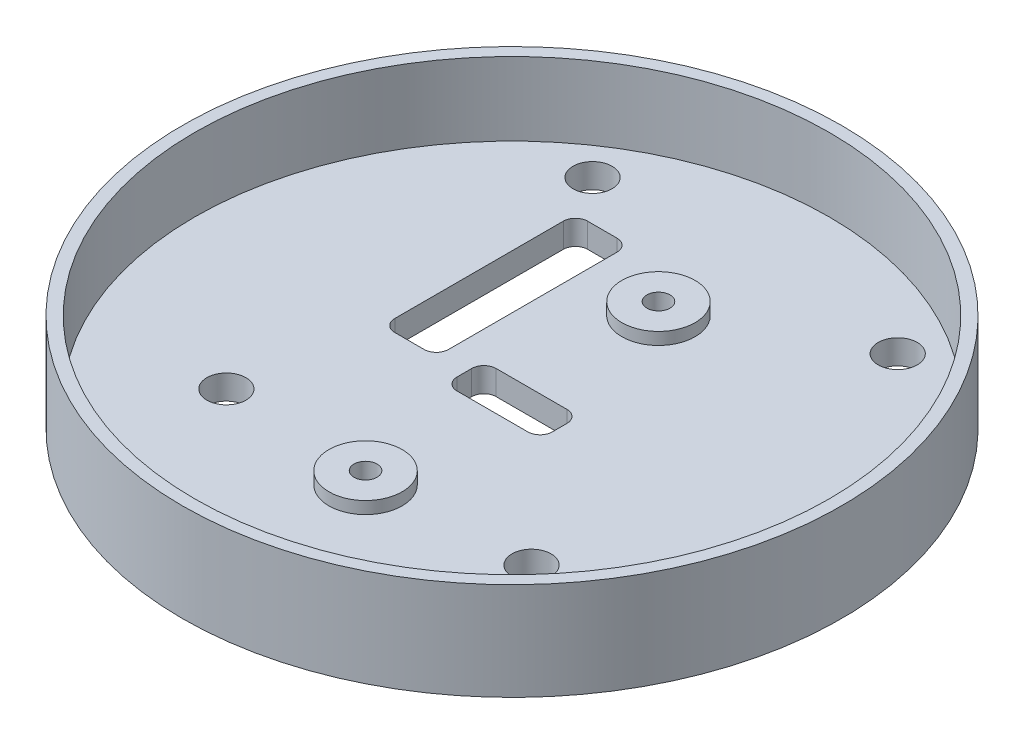
SolidWorks part; units mm, degrees
ref_plane "Front Plane" through (0, 0, 0) normal (0, 0, 1) x (1, 0, 0)
ref_plane "Top Plane" through (0, 0, 0) normal (0, 1, 0) x (1, 0, 0)
ref_plane "Right Plane" through (0, 0, 0) normal (1, 0, 0) x (0, 0, -1)
sketch "Sketch1" plane through (0, 0, 0) normal (0, 1, 0) x (1, 0, 0)
  circle A0 centre (0, 0) radius 34.29
  dimension "D1" = 68.58
extrude "Boss-Extrude1" add sketch "Sketch1" along normal blind 10.16
sketch "Sketch2" plane through (0, 10.16, 0) normal (0, 1, 0) x (1, 0, 0)
  circle A0 centre (0, 0) radius 33.02
  circle A1 centre (0, 0) radius 34.29 construction
  dimension "D1" = 66.04
extrude "Cut-Extrude1" cut sketch "Sketch2" against normal blind 7.62
sketch "Sketch3" plane through (0, 2.54, 0) normal (0, 1, 0) x (1, 0, 0)
  line L0 (0, -15.24) -> (0, 15.24) construction
  line L2 (0, -5.588) -> (0, 5.588) construction
  circle A0 centre (0, -15.24) radius 3.81
  circle A1 centre (0, 15.24) radius 3.81
  dimension "D2" = 7.62
  dimension "D3" = 7.62
  dimension "D1" = 30.48
extrude "Boss-Extrude2" add sketch "Sketch3" along normal blind 1.27
sketch "Sketch4" plane through (0, 3.81, 0) normal (0, 1, 0) x (1, 0, 0)
  line L0 (0, 33.02) -> (0, -33.02) construction
  circle A0 centre (0, -15.24) radius 1.27
  circle A1 centre (0, 15.24) radius 1.27
  circle A2 centre (0, -15.24) radius 3.81 construction
  circle A3 centre (0, 0) radius 33.02 construction
  circle A4 centre (0, 15.24) radius 3.81 construction
  circle A5 centre (0, 0) radius 33.02 construction
  point P7 (0, -15.24)
  point P10 (0, 15.24)
  dimension "D1" = 2.54
  dimension "D2" = 2.54
sketch "Sketch8" plane through (0, 2.54, 0) normal (0, 1, 0) x (1, 0, 0)
  line L0 (0, 33.02) -> (0, -33.02) construction
  line L2 (3.683, 2.032) -> (-3.683, 2.032)
  line L3 (4.953, 0.762) -> (4.953, -0.762)
  line L4 (3.683, -2.032) -> (-3.683, -2.032)
  line L5 (-4.953, 0.762) -> (-4.953, -0.762)
  line L6 (4.953, 2.032) -> (-4.953, -2.032) construction
  line L7 (4.953, -2.032) -> (-4.953, 2.032) construction
  arc A0 (-3.683, -2.032) -> (-4.953, -0.762) centre (-3.683, -0.762) cw
  arc A1 (-3.683, 2.032) -> (-4.953, 0.762) centre (-3.683, 0.762) ccw
  arc A2 (4.953, -0.762) -> (3.683, -2.032) centre (3.683, -0.762) cw
  arc A3 (3.683, 2.032) -> (4.953, 0.762) centre (3.683, 0.762) cw
  circle A4 centre (0, 0) radius 33.02 construction
  point P2 (0, 0)
  point P4 (0, 0)
  point P22 (0, 0)
  point P23 (8.7629, 0.8368)
  dimension "D3" = 1.27
  dimension "D1" = 9.906
  dimension "D2" = 4.064
extrude "Cut-Extrude3" cut sketch "Sketch8" against normal up to next
sketch "Sketch9" plane through (0, 2.54, 0) normal (0, 1, 0) x (1, 0, 0)
  line L1 (-12.192, 0) -> (-9.144, 0)
  line L2 (-13.462, 1.27) -> (-13.462, 18.796)
  line L3 (-12.192, 20.066) -> (-9.144, 20.066)
  line L4 (-7.874, 1.27) -> (-7.874, 18.796)
  line L5 (-13.462, 0) -> (-7.874, 20.066) construction
  line L6 (-13.462, 20.066) -> (-7.874, 0) construction
  line L9 (4.953, 0) -> (-22.7571, 0) construction
  line L10 (4.953, -0.762) -> (4.953, 0.762) construction
  line L11 (3.683, 2.032) -> (-3.683, 2.032) construction
  arc A0 (-9.144, 20.066) -> (-7.874, 18.796) centre (-9.144, 18.796) cw
  arc A1 (-13.462, 18.796) -> (-12.192, 20.066) centre (-12.192, 18.796) cw
  arc A2 (-12.192, 0) -> (-13.462, 1.27) centre (-12.192, 1.27) cw
  arc A3 (-9.144, 0) -> (-7.874, 1.27) centre (-9.144, 1.27) ccw
  point P11 (0, 2.032)
  dimension "D4" = 1.27
  dimension "D1" = 20.066
  dimension "D2" = 5.588
  dimension "D3" = 7.874
extrude "Cut-Extrude4" cut sketch "Sketch9" against normal up to next
sketch "Sketch11" plane through (0, 0, 0) normal (0, -1, 0) x (1, 0, 0)
  line L0 (-3.683, -2.032) -> (3.683, -2.032) construction
  line L1 (-15.875, 13.843) -> (15.875, 13.843) construction
  line L2 (-15.875, 13.843) -> (-15.875, -24.257) construction
  line L3 (-15.875, -24.257) -> (15.875, -24.257) construction
  line L4 (15.875, 13.843) -> (15.875, -24.257) construction
  line L5 (-15.875, 13.843) -> (15.875, -24.257) construction
  line L6 (-15.875, -24.257) -> (15.875, 13.843) construction
  line L7 (-13.462, -1.27) -> (-13.462, -18.796) construction
  circle A0 centre (15.875, 13.843) radius 2.032
  circle A1 centre (-15.875, 13.843) radius 2.032
  circle A2 centre (-15.875, -24.257) radius 2.032
  circle A3 centre (15.875, -24.257) radius 2.032
  point P0 (0, -5.207)
  dimension "D3" = 4.064
  dimension "D4" = 4.064
  dimension "D5" = 4.064
  dimension "D6" = 4.064
  dimension "D1" = 38.1
  dimension "D2" = 31.75
  dimension "D7" = 3.175
extrude "Cut-Extrude5" cut sketch "Sketch11" against normal up to next
hole_wizard "M2 Clearance Hole1" positions "Sketch12" profile "Sketch13" hole size "M2" standard "ANSI Metric" end condition through all
sketch "Sketch12" plane through (0, 3.81, 0) normal (0, 1, 0) x (1, 0, 0)
  point P0 (0, 15.24)
  point P3 (0, -15.24)
sketch "Sketch13" plane through (0, 3.81, -15.24) normal (1, 0, 0) x (0, 0, 1)
  line L0 (0, 0) -> (0, 3.81)
  line L1 (0, 3.81) -> (1.2, 3.81)
  line L2 (1.2, 3.81) -> (1.2, 0)
  line L5 (1.2, 0) -> (0, 0)
  line L11 (0, -6.35) -> (0, 107.95) construction
  dimension "Thru Hole Dia." = 2.4
  dimension "Thru Hole Depth" = 3.81
